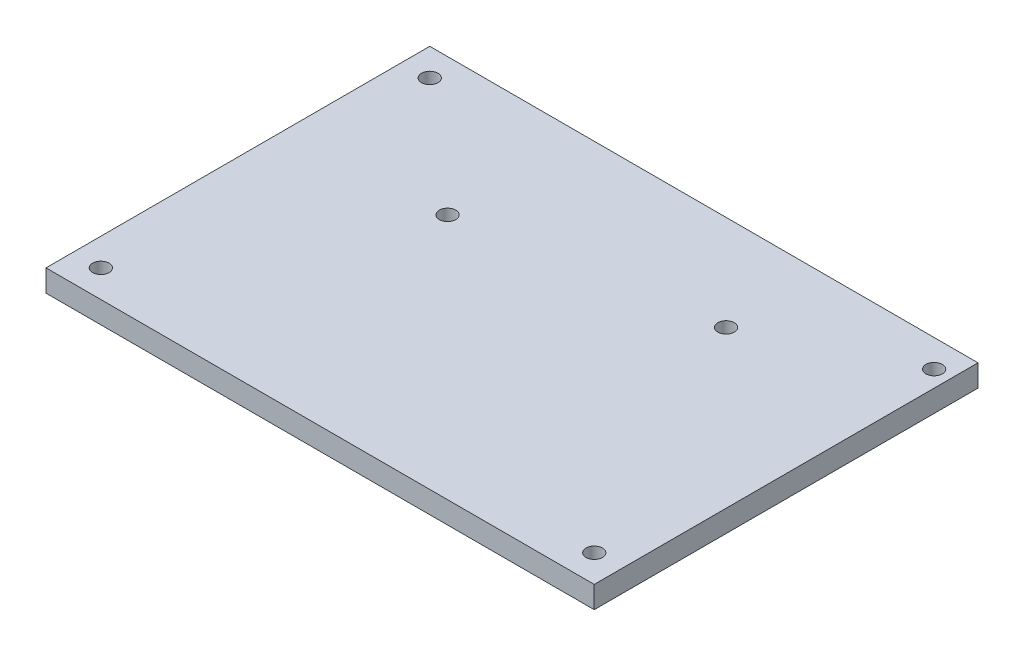
SolidWorks part; units mm, degrees
ref_plane "Alzado" through (0, 0, 0) normal (0, 0, 1) x (1, 0, 0)
ref_plane "Planta" through (0, 0, 0) normal (0, 1, 0) x (1, 0, 0)
ref_plane "Vista lateral" through (0, 0, 0) normal (1, 0, 0) x (0, 0, -1)
sketch "Croquis1" plane through (0, 0, 0) normal (0, 1, 0) x (1, 0, 0)
  line L1 (0, 0) -> (100, 0)
  line L2 (0, 0) -> (0, -70)
  line L3 (0, -70) -> (100, -70)
  line L4 (100, 0) -> (100, -70)
  dimension "D1" = 70
  dimension "D2" = 100
extrude "Saliente-Extruir1" add sketch "Croquis1" along normal blind 4
sketch "Croquis2" plane through (0, 4, 0) normal (0, 1, 0) x (1, 0, 0)
  line L0 (0, 0) -> (0, -70) construction
  line L1 (100, 0) -> (0, 0) construction
  line L2 (100, -70) -> (100, 0) construction
  line L3 (0, -70) -> (100, -70) construction
  circle A0 centre (28.25, -25) radius 1.5
  circle A1 centre (71.43, -17.38) radius 1.5
  circle A2 centre (5, -65) radius 1.5
  circle A3 centre (95, -65) radius 1.5
  circle A4 centre (97, -5) radius 1.5
  circle A5 centre (5, -5) radius 1.5
  dimension "D1" = 3
  dimension "D2" = 3
  dimension "D3" = 3
  dimension "D4" = 3
  dimension "D5" = 28.25
  dimension "D6" = 25
  dimension "D7" = 43.18
  dimension "D8" = 17.38
  dimension "D9" = 5
  dimension "D10" = 5
  dimension "D11" = 5
  dimension "D12" = 5
  dimension "D13" = 3
  dimension "D14" = 3
  dimension "D15" = 5
  dimension "D16" = 3
  dimension "D17" = 5
  dimension "D18" = 5
extrude "Cortar-Extruir1" cut sketch "Croquis2" against normal through all
